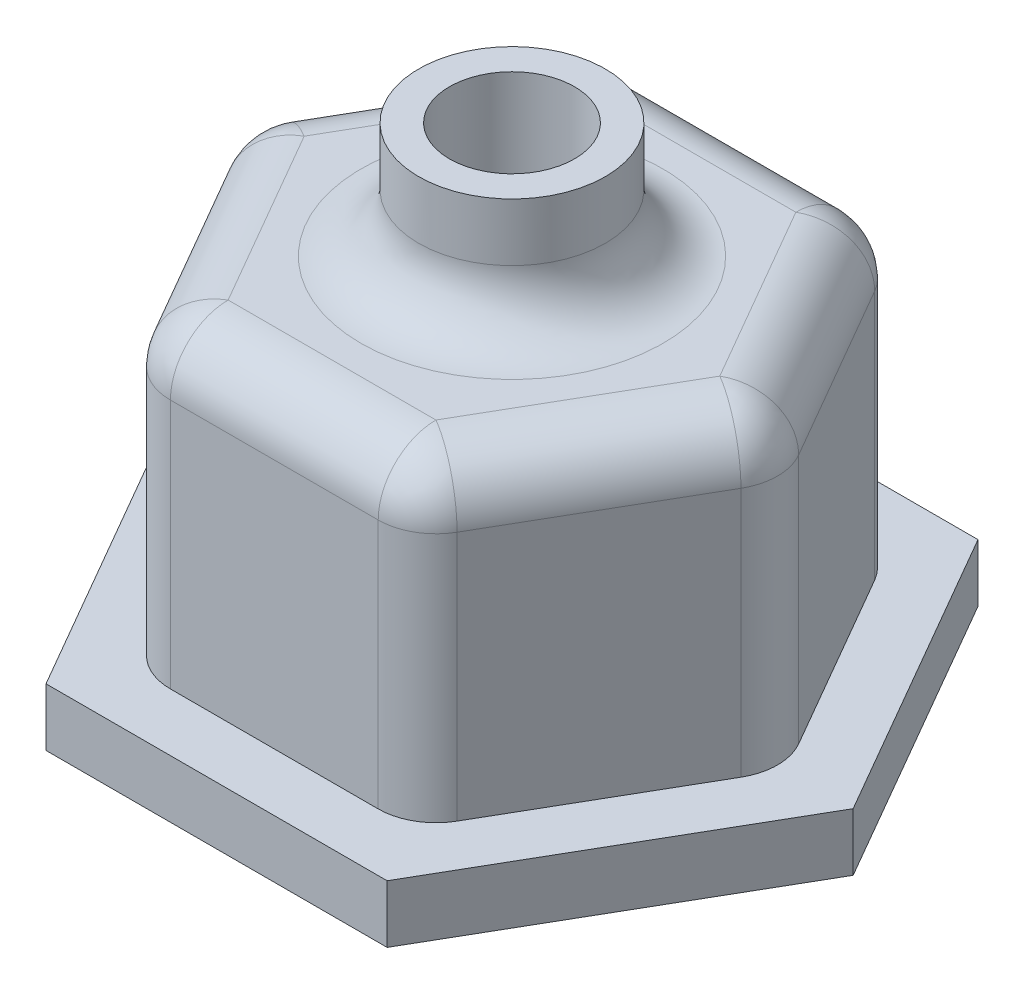
SolidWorks part; units mm, degrees
ref_plane "Front Plane" through (0, 0, 0) normal (0, 0, 1) x (1, 0, 0)
ref_plane "Top Plane" through (0, 0, 0) normal (0, 1, 0) x (1, 0, 0)
ref_plane "Right Plane" through (0, 0, 0) normal (1, 0, 0) x (0, 0, -1)
sketch "Sketch1" plane through (0, 0, 0) normal (0, 1, 0) x (1, 0, 0)
  line L0 (-1.15, 1.1481) -> (-1.15, -1.1481)
  line L1 (-7.1303, 0) -> (-3.5651, -6.175)
  line L2 (-3.5651, -6.175) -> (3.5651, -6.175)
  line L3 (3.5651, -6.175) -> (7.1303, 0)
  line L4 (7.1303, 0) -> (3.5651, 6.175)
  line L5 (3.5651, 6.175) -> (-3.5651, 6.175)
  line L6 (-3.5651, 6.175) -> (-7.1303, 0)
  circle A0 centre (0, 0) radius 6.175 construction
  arc A1 (-1.15, -1.1481) -> (-1.15, 1.1481) centre (0, 0) ccw
  dimension "D1" = 12.35
  dimension "D2" = 3.25
  dimension "D3" = 1.15
extrude "Boss-Extrude1" add sketch "Sketch1" along normal blind 8
sketch "Sketch2" plane through (0, 0, 0) normal (0, -1, 0) x (1, 0, 0)
  line L0 (-3.5651, 6.175) -> (3.5651, 6.175) construction
  line L1 (-4.4312, 7.675) -> (-8.8623, 0)
  line L2 (-8.8623, 0) -> (-4.4312, -7.675)
  line L3 (-4.4312, -7.675) -> (4.4312, -7.675)
  line L4 (4.4312, -7.675) -> (8.8623, 0)
  line L5 (8.8623, 0) -> (4.4312, 7.675)
  line L6 (4.4312, 7.675) -> (-4.4312, 7.675)
  line L7 (-1.15, -1.1481) -> (-1.15, 1.1481) construction
  line L8 (-1.15, -1.1481) -> (-1.15, 1.1481)
  circle A0 centre (0, 0) radius 7.675 construction
  arc A1 (-1.15, -1.1481) -> (-1.15, 1.1481) centre (0, 0) ccw construction
  arc A2 (-1.15, -1.1481) -> (-1.15, 1.1481) centre (0, 0) ccw
  dimension "D1" = 1.5
extrude "Boss-Extrude2" add sketch "Sketch2" along normal blind 1.5
sketch "Sketch4" plane through (0, 8, 0) normal (0, 1, 0) x (1, 0, 0)
  circle A0 centre (0, 0) radius 1.625
extrude "Extrude-Thin1" add sketch "Sketch4" along normal blind 3 thin
fillet "Fillet1" radius 1.5 13 edges at (0, 8, -6.175) (5.3477, 8, -3.0875) (5.3477, 8, 3.0875) (0, 8, 6.175) (-5.3477, 8, 3.0875) (-5.3477, 8, -3.0875) (2.425, 8, 0) (3.5651, 4, -6.175) (7.1303, 4, 0) (3.5651, 4, 6.175) (-3.5651, 4, 6.175) (-7.1303, 4, 0) (-3.5651, 4, -6.175)
